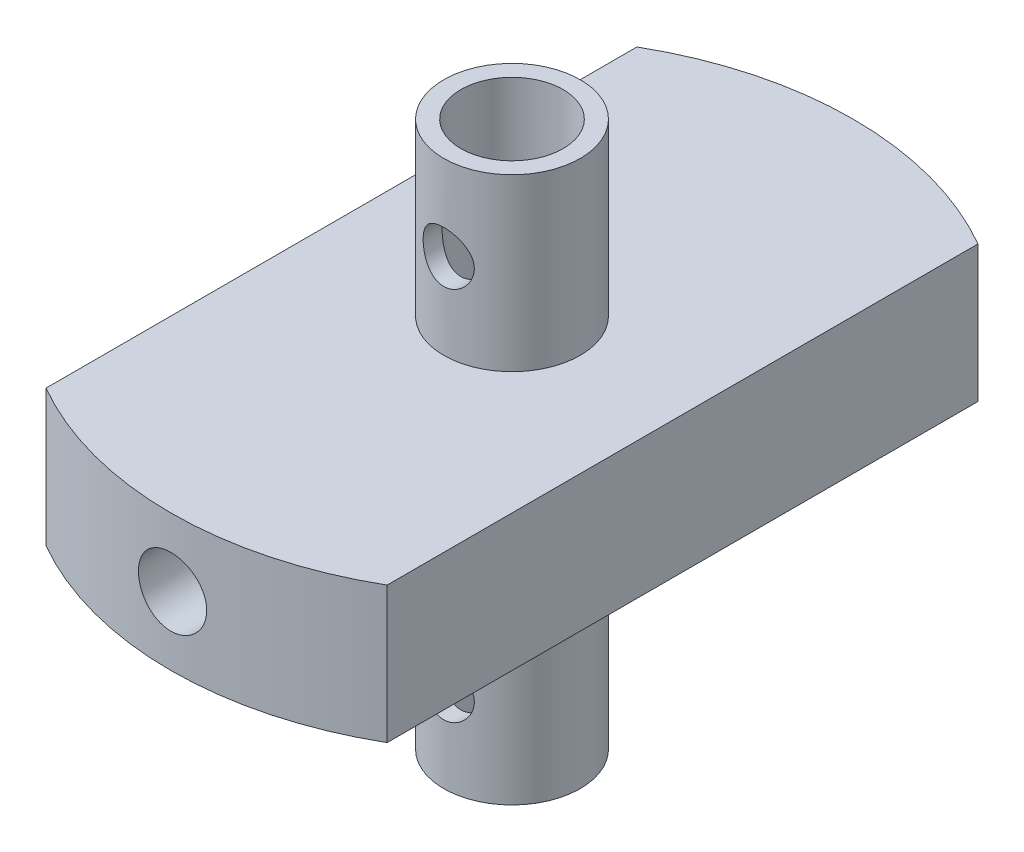
SolidWorks part; units mm, degrees
material "Delrin 2700 NC010, Low Viscosity Acetal Copolymer (SS)"
ref_plane "Front Plane" through (0, 0, 0) normal (0, 0, 1) x (1, 0, 0)
ref_plane "Top Plane" through (0, 0, 0) normal (0, 1, 0) x (1, 0, 0)
ref_plane "Right Plane" through (0, 0, 0) normal (1, 0, 0) x (0, 0, -1)
sketch "Sketch1" plane through (0, 0, 0) normal (0, 0, 1) x (1, 0, 0)
  line L0 (3, 0) -> (4, 0)
  line L1 (4, 0) -> (4, 14)
  line L2 (4, 14) -> (20, 14)
  line L3 (20, 14) -> (20, 22)
  line L4 (0, 0) -> (0, 39.5658) construction
  line L5 (0, 22) -> (20, 22)
  line L6 (3, 0) -> (3, 13)
  line L7 (3, 13) -> (0, 13)
  line L8 (0, 22) -> (0, 13)
  dimension "D1" = 22
  dimension "D2" = 6
  dimension "D3" = 8
  dimension "D4" = 8
  dimension "D5" = 40
  dimension "D6" = 13
revolve "Revolve1" add sketch "Sketch1" angle 360 about L4
sketch "Sketch2" plane through (0, 22, 0) normal (0, 1, 0) x (1, 0, 0)
  circle A0 centre (0, 0) radius 4
  circle A1 centre (0, 0) radius 3
  dimension "D1" = 8
  dimension "D2" = 6
extrude "Boss-Extrude1" add sketch "Sketch2" along normal blind 10
ref_plane "Plane1" through (0, 0, -4) normal (0, 0, -1) x (-1, 0, 0)
sketch "Sketch3" plane through (0, 0, -4) normal (0, 0, -1) x (-1, 0, 0)
  line L0 (-4, 0) -> (4, 0) construction
  line L1 (20, 22) -> (-20, 22) construction
  circle A0 centre (0, 5) radius 1.5
  circle A1 centre (0, 27) radius 1.5
  circle A2 centre (0, 18) radius 2
  dimension "D1" = 3
  dimension "D3" = 3
  dimension "D5" = 4
  dimension "D2" = 5
  dimension "D4" = 5
  dimension "D6" = 4
extrude "Cut-Extrude1" cut sketch "Sketch3" against normal through all both and the other way through all
sketch "Sketch4" plane through (0, 14, 0) normal (0, -1, 0) x (1, 0, 0)
  line L0 (0, 0) -> (0, 38.7763) construction
  line L1 (-30, 22.5) -> (-10, 22.5)
  line L2 (-10, 22.5) -> (-10, -22.5)
  line L3 (-10, -22.5) -> (-30, -22.5)
  line L4 (-30, -22.5) -> (-30, 22.5)
  line L5 (30, -22.5) -> (30, 22.5)
  line L6 (10, -22.5) -> (30, -22.5)
  line L7 (10, 22.5) -> (10, -22.5)
  line L8 (30, 22.5) -> (10, 22.5)
  dimension "D1" = 45
  dimension "D2" = 20
  dimension "D3" = 10
  dimension "D4" = 22.5
extrude "Cut-Extrude2" cut sketch "Sketch4" against normal blind 10
